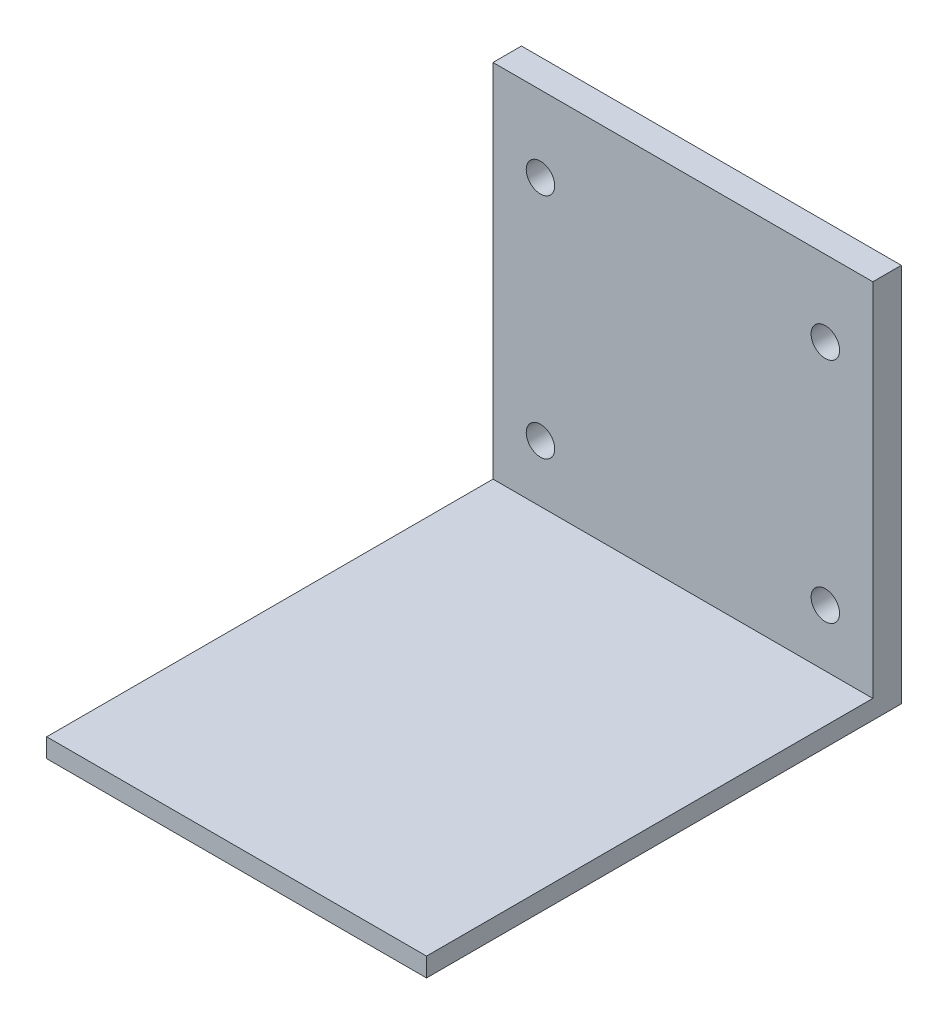
SolidWorks part; units mm, degrees
ref_plane "前视基准面" through (0, 0, 0) normal (0, 0, 1) x (1, 0, 0)
ref_plane "上视基准面" through (0, 0, 0) normal (0, 1, 0) x (1, 0, 0)
ref_plane "右视基准面" through (0, 0, 0) normal (1, 0, 0) x (0, 0, -1)
sketch "草图1" plane through (0, 0, 0) normal (0, 0, 1) x (1, 0, 0)
  line L1 (0, 0) -> (40, 0)
  line L2 (0, 0) -> (0, -40)
  line L3 (0, -40) -> (40, -40)
  line L4 (40, 0) -> (40, -40)
  dimension "D1" = 40
  dimension "D2" = 40
extrude "凸台-拉伸1" add sketch "草图1" along normal blind 3
sketch "草图2" plane through (0, 0, 3) normal (0, 0, 1) x (1, 0, 0)
  line L0 (40, -8) -> (35, -8) construction
  line L1 (40, -40) -> (40, 0) construction
  line L2 (35, -8) -> (35, 0) construction
  line L3 (40, 0) -> (0, 0) construction
  line L4 (20, 0) -> (20, -33.4434) construction
  line L5 (35, -8) -> (35, -32) construction
  circle A0 centre (35, -8) radius 1.5
  circle A1 centre (5, -8) radius 1.5
  circle A2 centre (35, -32) radius 1.5
  circle A3 centre (5, -32) radius 1.5
  dimension "D3" = 3
  dimension "D5" = 3
  dimension "D1" = 5
  dimension "D2" = 8
  dimension "D4" = 24
extrude "切除-拉伸1" cut sketch "草图2" against normal blind 3
sketch "草图3" plane through (0, 0, 3) normal (0, 0, 1) x (1, 0, 0)
  line L0 (0, 0) -> (0, -40) construction
  line L1 (40, -40) -> (0, -40)
  line L2 (40, -40) -> (40, -38)
  line L3 (40, -38) -> (0, -38)
  line L4 (0, -40) -> (0, -38)
  dimension "D1" = 2
extrude "凸台-拉伸2" add sketch "草图3" along normal blind 47
